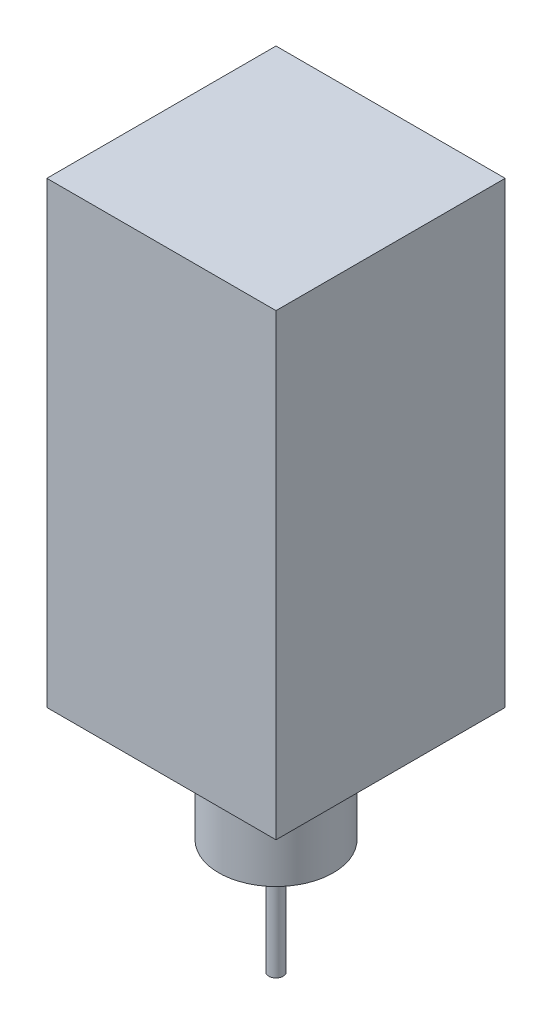
SolidWorks part; units mm, degrees
ref_plane "Front Plane" through (0, 0, 0) normal (0, 0, 1) x (1, 0, 0)
ref_plane "Top Plane" through (0, 0, 0) normal (0, 1, 0) x (1, 0, 0)
ref_plane "Right Plane" through (0, 0, 0) normal (1, 0, 0) x (0, 0, -1)
sketch "Sketch1" plane through (0, 0, 0) normal (0, 1, 0) x (1, 0, 0)
  line L1 (0, 0) -> (100, 0)
  line L2 (0, 0) -> (0, 100)
  line L3 (0, 100) -> (100, 100)
  line L4 (100, 0) -> (100, 100)
  dimension "D1" = 100
extrude "Boss-Extrude1" add sketch "Sketch1" along normal blind 200
sketch "Sketch2" plane through (0, 0, 0) normal (0, -1, 0) x (1, 0, 0)
  line L0 (100, 0) -> (0, -100) construction
  circle A0 centre (50, -50) radius 25
  point P6 (0, 0)
  dimension "D1" = 50
extrude "Boss-Extrude2" add sketch "Sketch2" along normal blind 50
sketch "Sketch3" plane through (0, -50, 0) normal (0, -1, 0) x (1, 0, 0)
  circle A0 centre (50, -50) radius 3.15
  circle A1 centre (50, -50) radius 25 construction
  dimension "D1" = 6.3
extrude "Boss-Extrude3" add sketch "Sketch3" along normal blind 50
